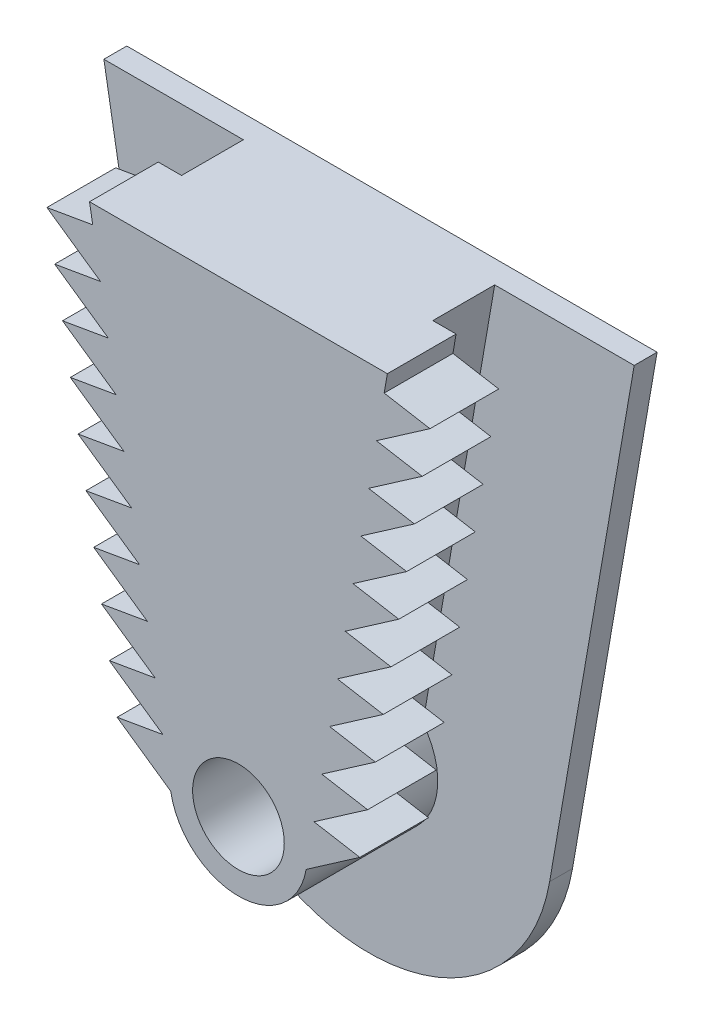
SolidWorks part; units mm, degrees
ref_plane "Front Plane" through (0, 0, 0) normal (0, 0, 1) x (1, 0, 0)
ref_plane "Top Plane" through (0, 0, 0) normal (0, 1, 0) x (1, 0, 0)
ref_plane "Right Plane" through (0, 0, 0) normal (1, 0, 0) x (0, 0, -1)
sketch "Sketch1" plane through (0, 0, 0) normal (0, 0, 1) x (1, 0, 0)
  line L0 (-3.7544, -0.6487) -> (-8.255, 25.4)
  line L1 (-8.255, 25.4) -> (8.255, 25.4)
  line L2 (0, 25.4) -> (0, 0) construction
  line L3 (3.7544, -0.6487) -> (8.255, 25.4)
  arc A1 (-3.7544, -0.6487) -> (3.7544, -0.6487) centre (0, 0) ccw
  dimension "D3" = 7.62
  dimension "D2" = 16.51
  dimension "D4" = 25.4
extrude "Boss-Extrude1" add sketch "Sketch1" along normal mid plane 3.81
sketch "Sketch3" plane through (0, 0, -1.905) normal (0, 0, -1) x (-1, 0, 0)
  line L21 (-6.9662, 25.4) -> (6.9662, 25.4)
  line L22 (-8.255, 25.4) -> (8.255, 25.4) construction
  line L23 (7.0035, 25.6162) -> (2.5029, -0.4324)
  line L24 (-2.5029, -0.4324) -> (-7.0035, 25.6162)
  line L25 (7.0035, 25.6162) -> (2.5029, -0.4324)
  line L26 (-2.5029, -0.4324) -> (-7.0035, 25.6162)
  arc A6 (-2.5029, -0.4324) -> (2.5029, -0.4324) centre (0, 0) ccw
  arc A7 (-2.5029, -0.4324) -> (2.5029, -0.4324) centre (0, 0) ccw
  line M6 (8.255, 25.4) -> (-8.255, 25.4)
  dimension "D1" = 1.27
extrude "Boss-Extrude3" add sketch "Sketch3" along normal blind 3.429 contours L26 A7 L25 M6
sketch "Sketch2" plane through (0, 0, 1.905) normal (0, 0, 1) x (1, 0, 0)
  line L0 (-3.7544, -0.6487) -> (-6.7268, 1.4154)
  line L1 (-6.7268, 1.4154) -> (-4.1868, 1.8542)
  line L2 (-8.255, 25.4) -> (-3.7544, -0.6487) construction
  line L3 (-3.7544, -0.6487) -> (-4.1868, 1.8542)
  dimension "D1" = 2.54
  dimension "D2" = 2.54
extrude "Boss-Extrude2" add sketch "Sketch2" against normal up to surface (3.81 mm away) up to face at (0, 11.7711, -1.905)
pattern_linear "LPattern1" count 10 spacing 2.54 along (-0.1703, 0.9854, 0) of "Boss-Extrude2"
mirror "Mirror1" about plane through (0, 0, 0) normal (1, 0, 0) of "LPattern1", "Boss-Extrude2"
sketch "Sketch4" plane through (0, 0, -5.334) normal (0, 0, -1) x (-1, 0, 0)
  line L0 (-14.6991, 25.4) -> (14.6991, 25.4)
  line L1 (-14.4749, 24.1027) -> (-14.6991, 25.4)
  line L2 (14.4749, 24.1027) -> (14.6991, 25.4)
  line L3 (6.9662, 25.4) -> (-6.9662, 25.4) construction
  line L5 (14.4749, 24.1027) -> (10.0117, -1.7298)
  line L6 (-10.0117, -1.7298) -> (-14.4749, 24.1027)
  line L7 (14.4749, 24.1027) -> (10.0117, -1.7298)
  line L8 (-10.0117, -1.7298) -> (-14.4749, 24.1027)
  arc A4 (-10.0117, -1.7298) -> (10.0117, -1.7298) centre (0, 0) ccw
  arc A5 (-10.0117, -1.7298) -> (10.0117, -1.7298) centre (0, 0) ccw
  dimension "D1" = 7.62
extrude "Boss-Extrude4" add sketch "Sketch4" along normal blind 1.27
sketch "Sketch5" plane through (0, 0, 1.905) normal (0, 0, 1) x (1, 0, 0)
  circle A0 centre (0, 0) radius 2.54
  dimension "D1" = 5.08
extrude "Cut-Extrude1" cut sketch "Sketch5" against normal through all
sketch "Sketch6" plane through (0, 0, 1.905) normal (0, 0, 1) x (1, 0, 0)
  circle A0 centre (0, 0) radius 2.54
  circle A1 centre (0, 0) radius 3.81
extrude "Boss-Extrude5" add sketch "Sketch6" against normal blind 7.62
